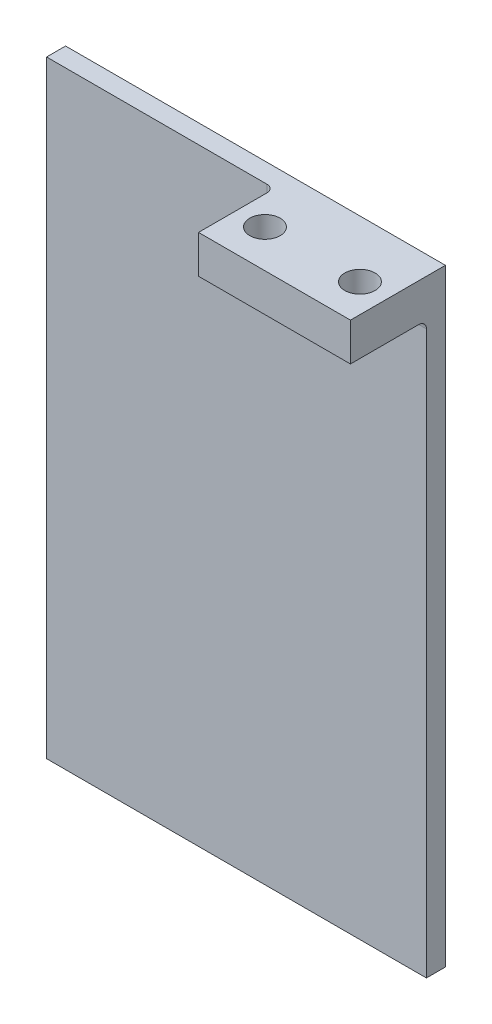
SolidWorks part; units mm, degrees
ref_plane "前视基准面" through (0, 0, 0) normal (0, 0, 1) x (1, 0, 0)
ref_plane "上视基准面" through (0, 0, 0) normal (0, 1, 0) x (1, 0, 0)
ref_plane "右视基准面" through (0, 0, 0) normal (1, 0, 0) x (0, 0, -1)
sketch "草图1" plane through (0, 0, 0) normal (0, 0, 1) x (1, 0, 0)
  line L1 (-50, 80) -> (50, 80)
  line L2 (-50, 80) -> (-50, -80)
  line L3 (-50, -80) -> (50, -80)
  line L4 (50, 80) -> (50, -80)
  line L5 (0, -80) -> (0, 80) construction
  line L6 (-50, 0) -> (50, 0) construction
  point P0 (0, 0)
  dimension "D1" = 160
  dimension "D2" = 100
extrude "凸台-拉伸1" add sketch "草图1" along normal blind 5
sketch "草图2" plane through (0, 80, 0) normal (0, 1, 0) x (1, 0, 0)
  line L1 (50, -5) -> (10, -5)
  line L2 (50, -5) -> (50, -25)
  line L3 (50, -25) -> (10, -25)
  line L4 (10, -5) -> (10, -25)
  dimension "D1" = 20
  dimension "D2" = 40
extrude "凸台-拉伸2" add sketch "草图2" against normal blind 10
sketch "草图3" plane through (0, 70, 0) normal (0, -1, 0) x (1, 0, 0)
  line L1 (10, 5) -> (10, 25) construction
  line L2 (50, 25) -> (50, 5) construction
  circle A0 centre (17.5, 15) radius 4
  circle A1 centre (42.5, 15) radius 4
  point P9 (10, 15)
  dimension "D3" = 8
  dimension "D4" = 8
  dimension "D1" = 25
  dimension "D2" = 7.5
extrude "切除-拉伸1" cut sketch "草图3" against normal blind 10
fillet "圆角1" radius 2 2 edges at (10, 75, 5) (30, 70, 5)
